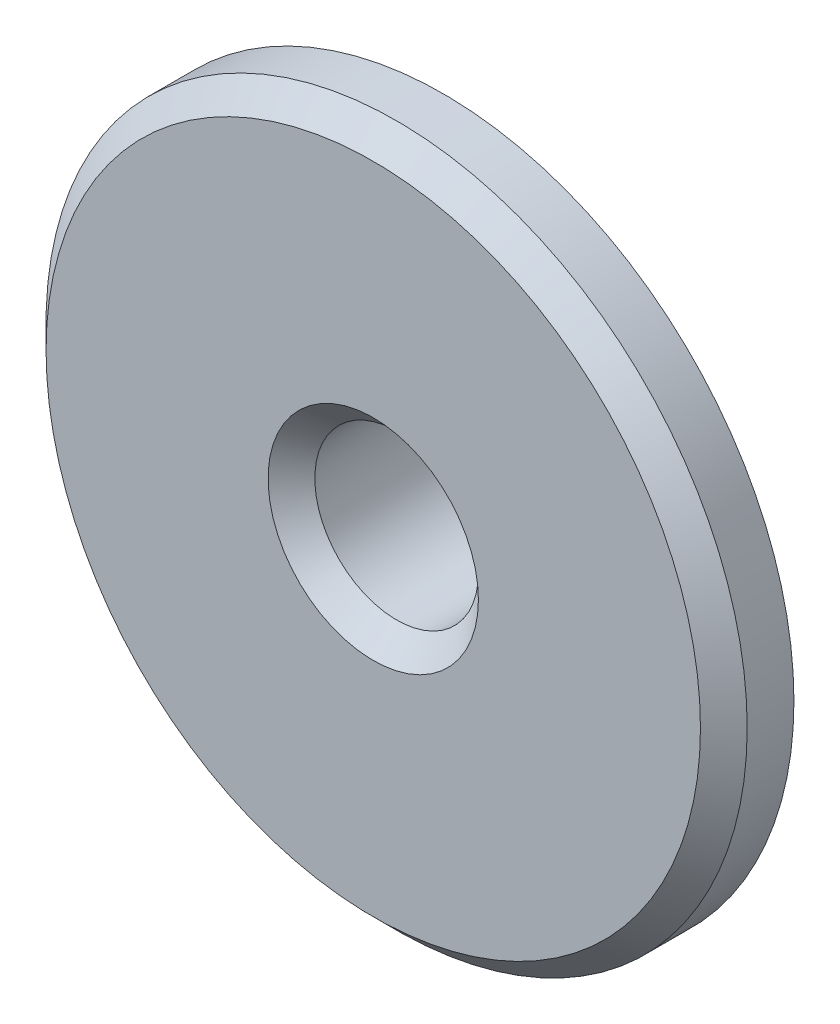
SolidWorks part; units mm, degrees
material "3D printed plastic"
ref_plane "Front Plane" through (0, 0, 0) normal (0, 0, 1) x (1, 0, 0)
ref_plane "Top Plane" through (0, 0, 0) normal (0, 1, 0) x (1, 0, 0)
ref_plane "Right Plane" through (0, 0, 0) normal (1, 0, 0) x (0, 0, -1)
sketch "Sketch1" plane through (0, 0, 0) normal (-1, 0, 0) x (0, 0, 1)
  line L0 (0, 0) -> (-9.2207, 0) construction
  line L1 (-8, 3.5) -> (0, 3.5)
  line L2 (0, 3.5) -> (0, 15)
  line L3 (0, 15) -> (-3, 15)
  line L4 (-3, 15) -> (-3, 5)
  line L5 (-3, 5) -> (-8, 5)
  line L6 (-8, 5) -> (-8, 3.5)
  dimension "D1" = 5
  dimension "D2" = 3
  dimension "D3" = 10
  dimension "D4" = 1.5
  dimension "D5" = 30
revolve "Revolve1" add sketch "Sketch1" angle 360 about L0
chamfer "Chamfer1" distance 1 angle 45 1 edges at (5, 0, -8)
chamfer "Chamfer2" distance 1 angle 45 2 edges at (3.5, 0, 0) (15, 0, 0)
